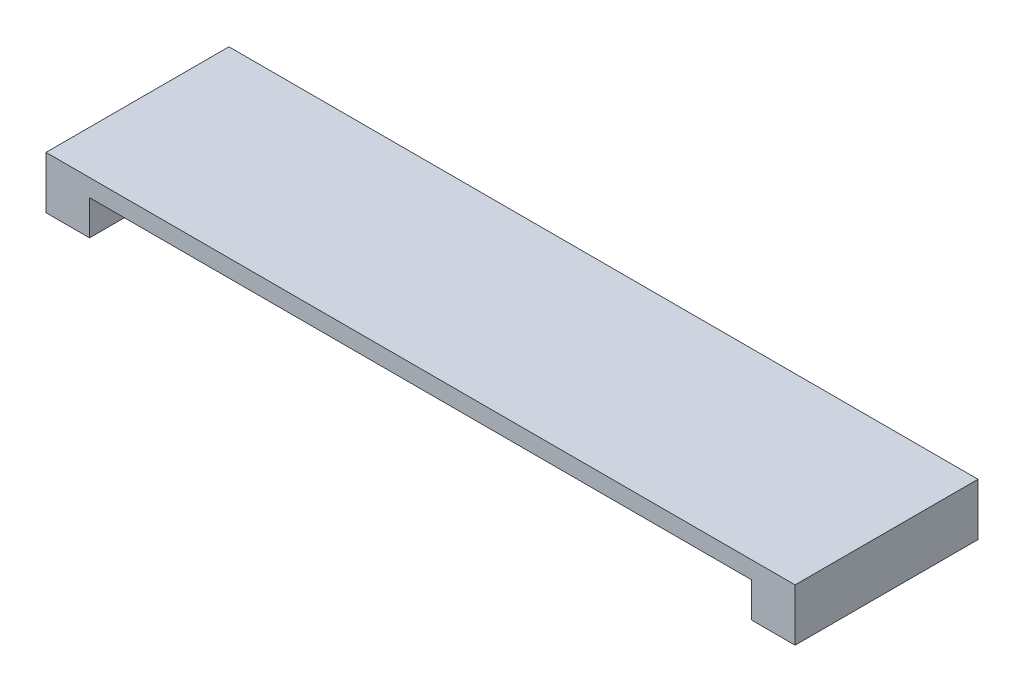
SolidWorks part; units mm, degrees
ref_plane "Front" through (0, 0, 0) normal (0, 0, 1) x (1, 0, 0)
ref_plane "Top" through (0, 0, 0) normal (0, 1, 0) x (1, 0, 0)
ref_plane "Right" through (0, 0, 0) normal (1, 0, 0) x (0, 0, -1)
sketch "Sketch1" plane through (0, 0, 0) normal (0, 1, 0) x (1, 0, 0)
  line L1 (-430, -105) -> (430, -105)
  line L2 (-430, -105) -> (-430, 105)
  line L3 (-430, 105) -> (430, 105)
  line L4 (430, -105) -> (430, 105)
  line L5 (-430, -105) -> (430, 105) construction
  line L6 (-430, 105) -> (430, -105) construction
  point P0 (0, 0)
  dimension "D1" = 210
  dimension "D2" = 860
extrude "Boss-Extrude1" add sketch "Sketch1" along normal blind 20
sketch "Sketch2" plane through (0, 0, 0) normal (0, 0, 1) x (1, 0, 0)
  line L0 (0, 52.792) -> (0, -65.1238) construction
  line L1 (-430, 0) -> (-380, 0)
  line L2 (-430, 0) -> (-430, -40)
  line L3 (-430, -40) -> (-380, -40)
  line L4 (-380, 0) -> (-380, -40)
  line L5 (430, -40) -> (380, -40)
  line L6 (380, 0) -> (380, -40)
  line L7 (430, 0) -> (380, 0)
  line L8 (430, 0) -> (430, -40)
  dimension "D1" = 40
  dimension "D2" = 50
extrude "Boss-Extrude2" add sketch "Sketch2" along normal up to surface and the other way up to surface up to face at (0, 10, 105) other way up to face at (0, 10, -105)
